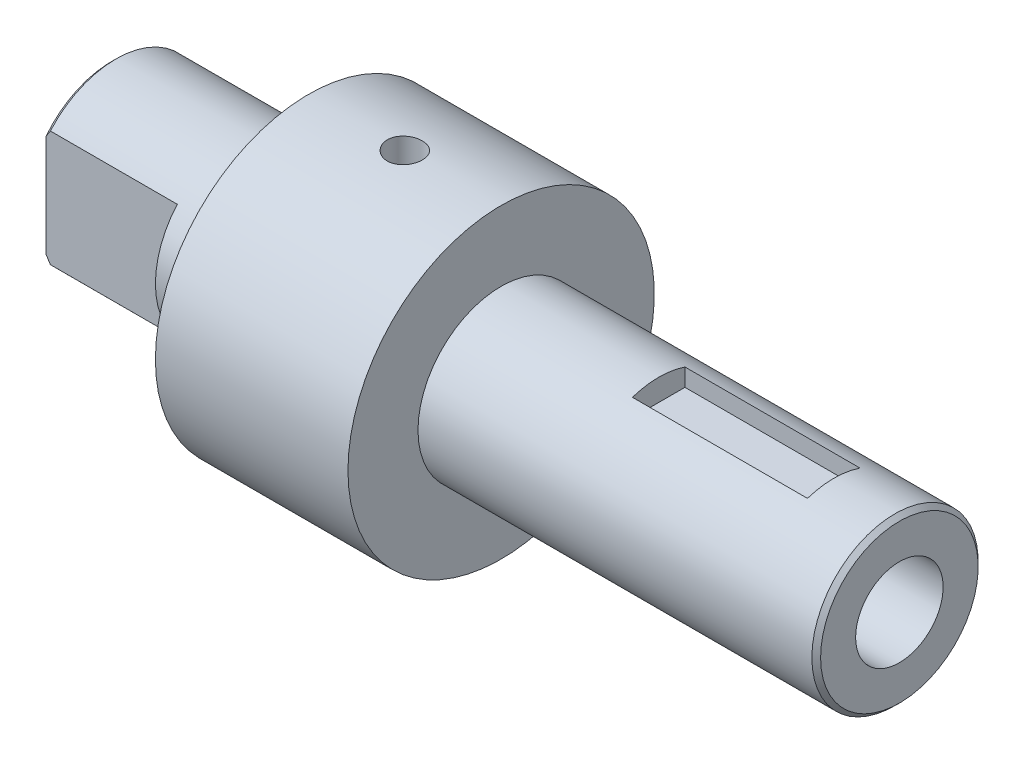
SolidWorks part; units mm, degrees
ref_plane "Спереди" through (0, 0, 0) normal (0, 0, 1) x (1, 0, 0)
ref_plane "Сверху" through (0, 0, 0) normal (0, 1, 0) x (1, 0, 0)
ref_plane "Справа" through (0, 0, 0) normal (1, 0, 0) x (0, 0, -1)
sketch "Эскиз1" plane through (0, 0, 0) normal (0, 0, 1) x (1, 0, 0)
  line L0 (0, 10) -> (180, 10) construction
  line L1 (0, 10) -> (0, 20)
  line L2 (0, 20) -> (45, 20)
  line L3 (45, 20) -> (45, 35)
  line L4 (45, 35) -> (89, 35)
  line L5 (89, 35) -> (89, 19)
  line L6 (89, 19) -> (180, 19)
  line L7 (180, 19) -> (180, 10)
  line L8 (0, 10) -> (180, 10)
  line L9 (0, 0) -> (12.8687, 0) construction
  dimension "D1" = 70
  dimension "D2" = 40
  dimension "D3" = 38
  dimension "D4" = 180
  dimension "D5" = 45
  dimension "D6" = 44
  dimension "D7" = 20
revolve "Повернуть1" add sketch "Эскиз1" angle 360 about L9
sketch "Эскиз8" plane through (0, 0, 0) normal (-1, 0, 0) x (0, 0, 1)
  line L0 (15, 13.2288) -> (15, -13.2288)
  line L1 (0, 20) -> (0, -20) construction
  line L2 (-15, 13.2288) -> (-15, -13.2288)
  circle A0 centre (0, 0) radius 20 construction
  circle A1 centre (0, 0) radius 20 construction
  arc A2 (-15, 13.2288) -> (-15, -13.2288) centre (0, 0) ccw
  arc A3 (15, -13.2288) -> (15, 13.2288) centre (0, 0) ccw
  dimension "D1" = 30
extrude "Вырез-Вытянуть5" cut sketch "Эскиз8" against normal blind 30
sketch "Эскиз9" plane through (0, 0, 0) normal (0, 1, 0) x (1, 0, 0)
  line L0 (45, 0) -> (89, 0) construction
  line L1 (45, 35) -> (45, -35) construction
  line L2 (89, -19) -> (89, 19) construction
  circle A0 centre (67, 0) radius 4
  dimension "D1" = 8
extrude "Вырез-Вытянуть6" cut sketch "Эскиз9" against normal through all both and the other way through all
sketch "Эскиз6" plane through (0, 0, 0) normal (0, 0, 1) x (1, 0, 0)
  line L0 (180, 19) -> (89, 19) construction
  line L1 (125, 19) -> (165, 19)
  line L2 (125, 19) -> (125, 14)
  line L3 (125, 14) -> (165, 14)
  line L4 (165, 19) -> (165, 14)
  line L5 (180, -19) -> (180, 19) construction
  dimension "D1" = 40
  dimension "D2" = 15
  dimension "D3" = 5
extrude "Вырез-Вытянуть4" cut sketch "Эскиз6" against normal mid plane 12
chamfer "Фаска3" distance 1 angle 45 3 edges at (180, 0, 19) (0, -20, 0) (0, 20, 0)
